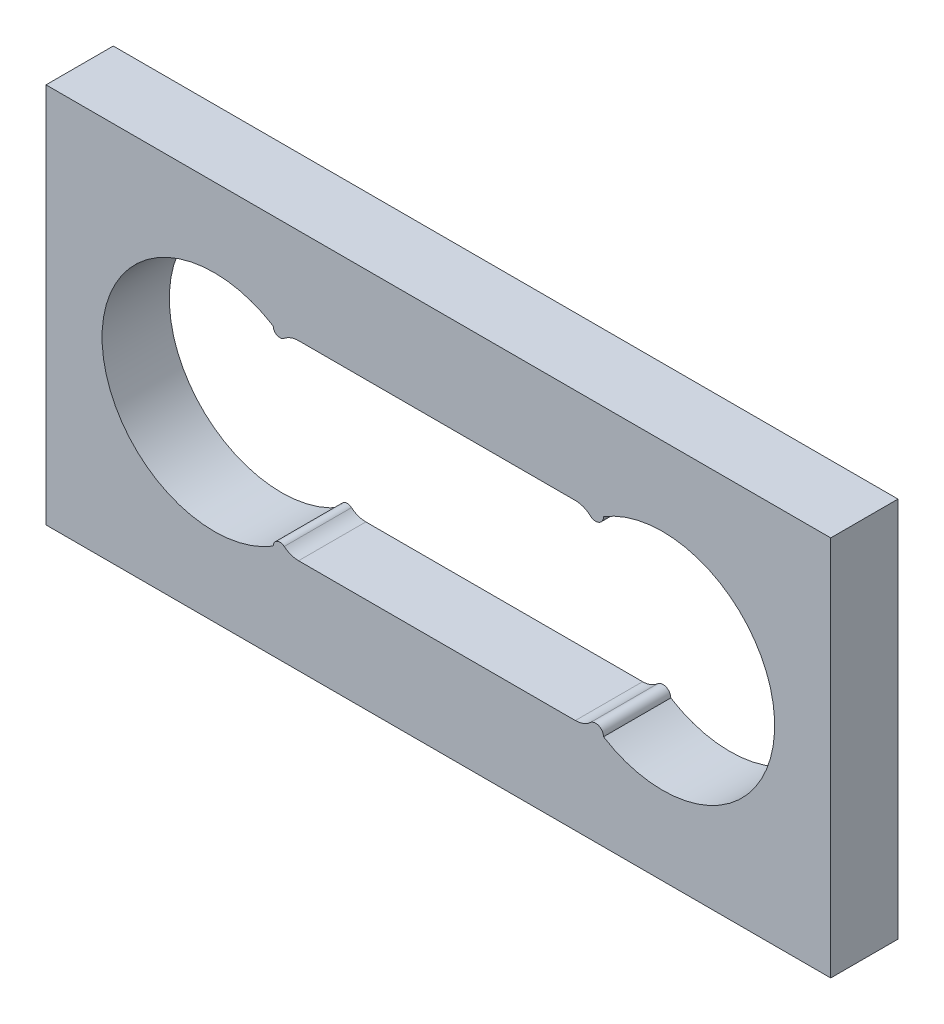
SolidWorks part; units mm, degrees
ref_plane "정면" through (0, 0, 0) normal (0, 0, 1) x (1, 0, 0)
ref_plane "윗면" through (0, 0, 0) normal (0, 1, 0) x (1, 0, 0)
ref_plane "우측면" through (0, 0, 0) normal (1, 0, 0) x (0, 0, -1)
sketch "스케치1" plane through (0, 0, 0) normal (0, 0, 1) x (1, 0, 0)
  line L1 (-17.5, -8.5) -> (17.5, -8.5)
  line L2 (-17.5, -8.5) -> (-17.5, 8.5)
  line L3 (-17.5, 8.5) -> (17.5, 8.5)
  line L4 (17.5, -8.5) -> (17.5, 8.5)
  line L5 (-17.5, -8.5) -> (17.5, 8.5) construction
  line L6 (-17.5, 8.5) -> (17.5, -8.5) construction
  line L7 (-10, -4.25) -> (10, -4.25)
  line L8 (-10, -4.25) -> (-10, 4.25)
  line L9 (-10, 4.25) -> (10, 4.25)
  line L10 (10, -4.25) -> (10, 4.25)
  line L11 (-10, -4.25) -> (10, 4.25) construction
  line L12 (-10, 4.25) -> (10, -4.25) construction
  circle A0 centre (-10, 0) radius 5
  circle A1 centre (10, 0) radius 5
  point P0 (0, 0)
  point P6 (0, 0)
  dimension "D1" = 10
  dimension "D2" = 10
  dimension "D3" = 20
  dimension "D4" = 17
  dimension "D5" = 35
  dimension "D6" = 8.5
extrude "보스-돌출1" add sketch "스케치1" along normal blind 3 contours L1 L4 L3 L2 A1 L7 A0 L9
sketch "스케치2" plane through (0, 0, 3) normal (0, 0, 1) x (1, 0, 0)
  line L0 (-7.3661, 4.25) -> (7.3661, 4.25) construction
  line L1 (-7.3661, -4.25) -> (7.3661, -4.25) construction
  circle A0 centre (-7.0661, 4.25) radius 0.3
  circle A1 centre (-7.0661, -4.25) radius 0.3
  circle A2 centre (7.0161, -4.25) radius 0.35
  circle A3 centre (7.0161, 4.25) radius 0.35
  dimension "D1" = 0.6
  dimension "D2" = 0.6
  dimension "D3" = 0.7
  dimension "D4" = 0.7
extrude "보스-돌출2" add sketch "스케치2" against normal blind 3
fillet "필렛1" radius 1 4 edges at (6.6661, 4.25, 1.5) (6.6661, -4.25, 1.5) (-6.7661, -4.25, 1.5) (-6.7661, 4.25, 1.5)
